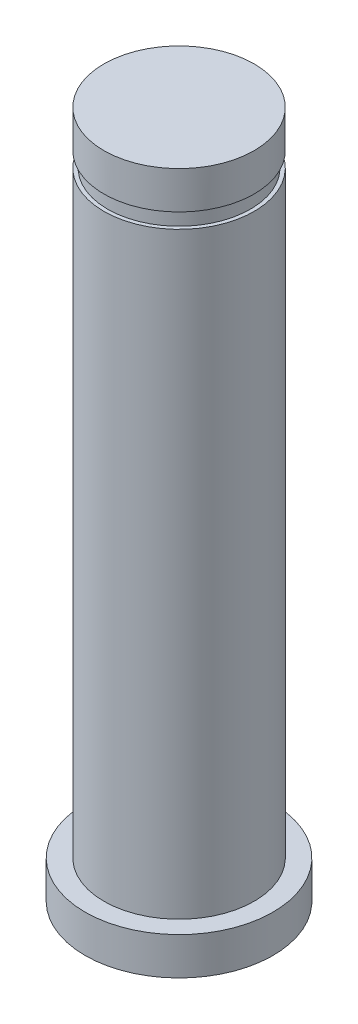
SolidWorks part; units mm, degrees
material "6061 合金"
ref_plane "前视基准面" through (0, 0, 0) normal (0, 0, 1) x (1, 0, 0)
ref_plane "上视基准面" through (0, 0, 0) normal (0, 1, 0) x (1, 0, 0)
ref_plane "右视基准面" through (0, 0, 0) normal (1, 0, 0) x (0, 0, -1)
sketch "草图1" plane through (0, 0, 0) normal (0, 1, 0) x (1, 0, 0)
  circle A0 centre (0, 0) radius 5
  dimension "D1" = 10
extrude "凸台-拉伸1" add sketch "草图1" along normal blind 2
sketch "草图2" plane through (0, 2, 0) normal (0, 1, 0) x (1, 0, 0)
  circle A0 centre (0, 0) radius 4
  dimension "D1" = 8
extrude "凸台-拉伸2" add sketch "草图2" along normal blind 34.6
sketch "草图3" plane through (0, 0, 0) normal (0, 0, 1) x (1, 0, 0)
  line L0 (0, 36.6) -> (0, 0) construction
  line L1 (4, 36.6) -> (-4, 36.6) construction
  line L2 (4, 2) -> (4, 36.6) construction
  line L3 (3.8, 33.8) -> (4.2, 33.8)
  line L4 (3.8, 33.8) -> (3.8, 34.6)
  line L5 (3.8, 34.6) -> (4.2, 34.6)
  line L6 (4.2, 33.8) -> (4.2, 34.6)
  line L7 (3.8, 33.8) -> (4.2, 34.6) construction
  line L8 (3.8, 34.6) -> (4.2, 33.8) construction
  point P5 (4, 34.2)
  dimension "D1" = 0.8
  dimension "D2" = 0.4
  dimension "D3" = 2
revolve "切除-旋转1" cut sketch "草图3" angle 360 about L0
